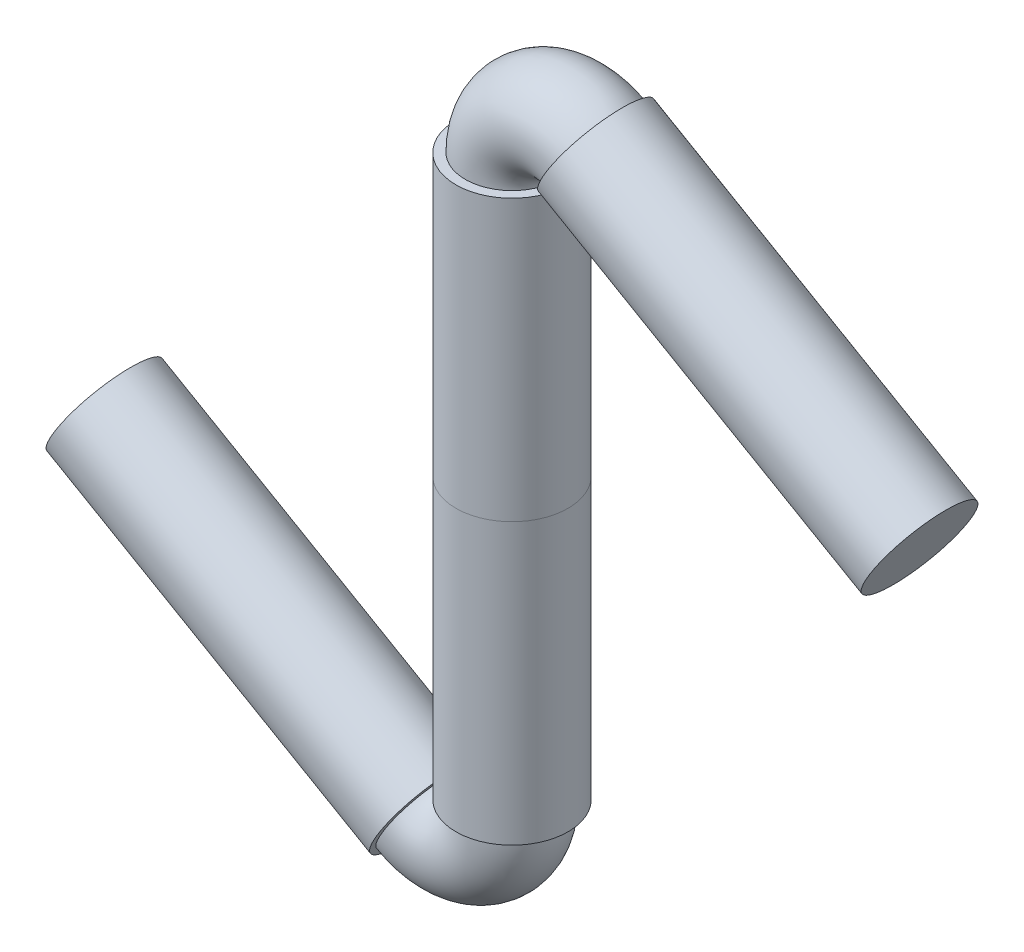
SolidWorks part; units mm, degrees
ref_plane "前视基准面" through (0, 0, 0) normal (0, 0, 1) x (1, 0, 0)
ref_plane "上视基准面" through (0, 0, 0) normal (0, 1, 0) x (1, 0, 0)
ref_plane "右视基准面" through (0, 0, 0) normal (1, 0, 0) x (0, 0, -1)
other "Configuration Table"
sketch "草图1" plane through (0, 0, 0) normal (0, 1, 0) x (1, 0, 0)
  circle A0 centre (0, 0) radius 15
  dimension "D1" = 30
extrude "凸台-拉伸1" add sketch "草图1" along normal blind 75
sketch "草图6" plane through (0, 75, 0) normal (0, 1, 0) x (1, 0, 0)
  line L0 (-15, 0) -> (15, 0) construction
  line L1 (0, -15) -> (0, 15) construction
  line L2 (15, -54.7831) -> (15, 54.7831) construction
  circle A1 centre (0, 0) radius 15 construction
  point P6 (0, 0)
  point P8 (0, 0)
  point P11 (0, 0)
  point P13 (15, 0)
ref_plane "基准面2" through (0, 0, 0) normal (0, 0, 1) x (1, 0, 0)
sketch "草图9" plane through (0, 0, 0) normal (0, 0, 1) x (1, 0, 0)
  line L0 (15, 75) -> (65.9532, 163.2536) construction
  line L1 (-15, 75) -> (15, 75) construction
  line L2 (22.5, 87.9904) -> (-31.2718, 119.0356) construction
  arc A0 (0, 75) -> (22.5, 87.9904) centre (15, 75) cw
  point P11 (22.5, 87.9904)
  dimension "D1" = 120
ref_plane "基准面3" through (-21.226, 12.2548, 0) normal (-0.866, 0.5, 0) x (0, 0, 1)
sketch "草图10" plane through (-21.226, 12.2548, 0) normal (-0.866, 0.5, 0) x (0, 0, 1)
  circle A0 centre (0, 87.4519) radius 12.5
  dimension "D1" = 25
sweep "扫描1" add profiles "草图10" path "草图9"
sketch "草图13" plane through (-21.226, 12.2548, 0) normal (0.866, -0.5, 0) x (0, 0, -1)
  circle A0 centre (0, 87.4519) radius 14
  dimension "D1" = 28
extrude "凸台-拉伸7" add sketch "草图13" along normal blind 100
mirror "镜向14" about plane through (0, 0, 0) normal (0, 1, 0) of bodies 117
mirror "镜向15" about plane through (0, 0, 0) normal (1, 0, 0) of bodies 118
delete or keep bodies "实体-删除/保留 2" type delete bodies bodies 118
